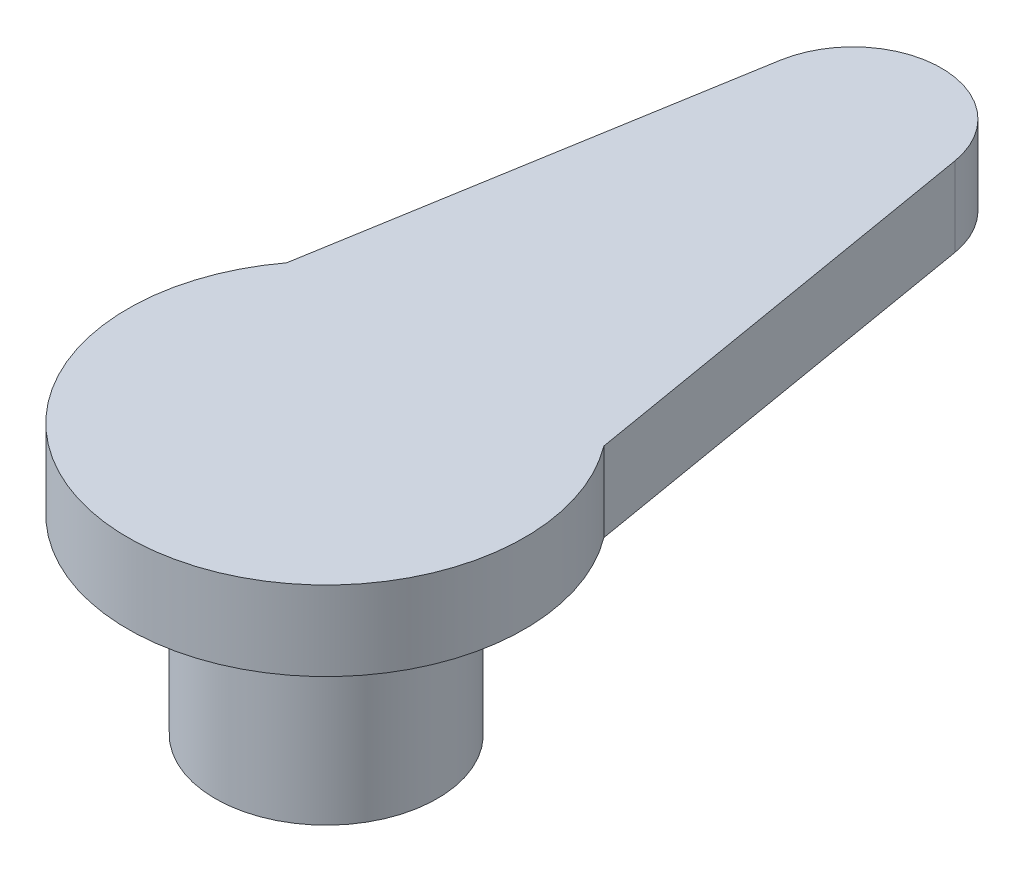
SolidWorks part; units mm, degrees
ref_plane "Front Plane" through (0, 0, 0) normal (0, 0, 1) x (1, 0, 0)
ref_plane "Top Plane" through (0, 0, 0) normal (0, 1, 0) x (1, 0, 0)
ref_plane "Right Plane" through (0, 0, 0) normal (1, 0, 0) x (0, 0, -1)
sketch "Sketch1" plane through (0, 0, 0) normal (0, 1, 0) x (1, 0, 0)
  line L0 (5, 3.75) -> (2.75, 17.0612)
  line L1 (-5, 3.75) -> (-2.75, 17.0612)
  circle A0 centre (0, 0) radius 6.25
  arc A1 (-2.75, 17.0612) -> (2.75, 17.0612) centre (0, 16.5963) cw
  dimension "D1" = 12.5
  dimension "D2" = 10
  dimension "D3" = 5.5
  dimension "D4" = 13.5
extrude "Boss-Extrude1" add sketch "Sketch1" along normal blind 2.5 contours A1 L1 A0 L0 | A0
sketch "Sketch2" plane through (0, 0, 0) normal (0, -1, 0) x (1, 0, 0)
  circle A0 centre (0, 0) radius 3.5
  dimension "D1" = 7
extrude "Boss-Extrude2" add sketch "Sketch2" along normal blind 6
sketch "Sketch3" plane through (0, -6, 0) normal (0, -1, 0) x (1, 0, 0)
  line L0 (1.4595, -1.475) -> (-1.4595, -1.475)
  circle A0 centre (0, 0) radius 2.075
  point P5 (0, 2.075)
  dimension "D1" = 4.15
  dimension "D2" = 3.55
extrude "Cut-Extrude1" cut sketch "Sketch3" against normal up to surface (6 mm away) contours L0 A0
